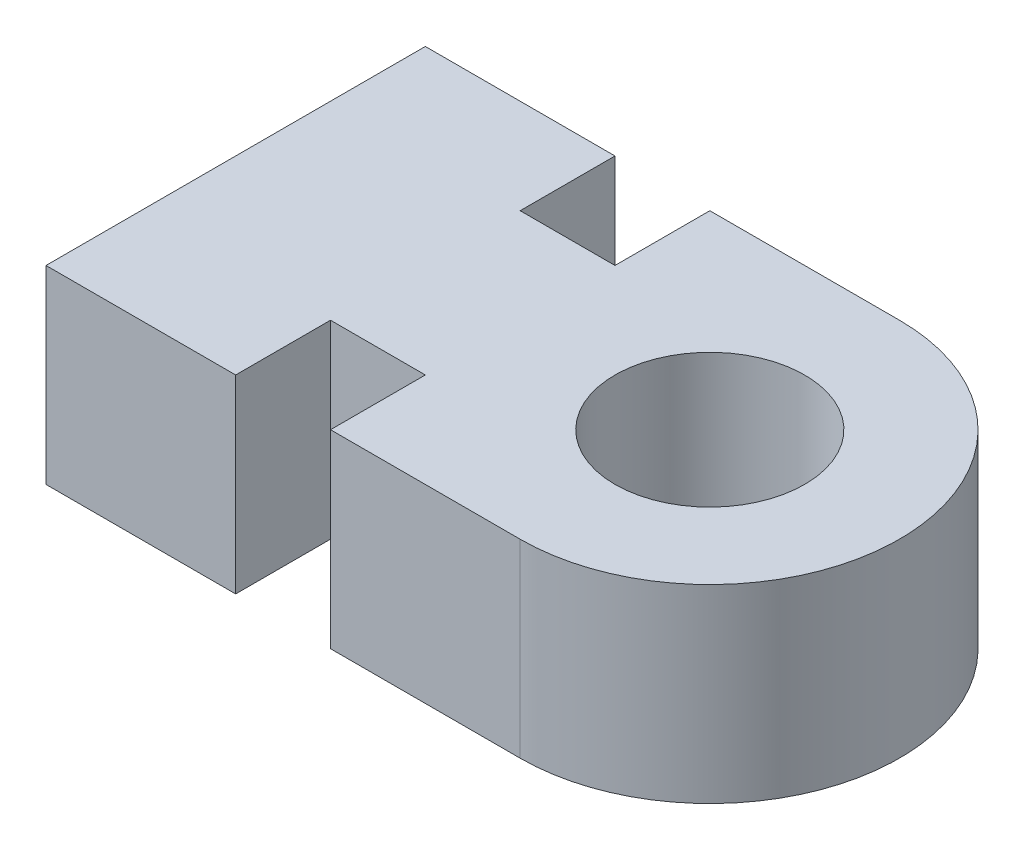
SolidWorks part; units mm, degrees
ref_plane "Front Plane" through (0, 0, 0) normal (0, 0, 1) x (1, 0, 0)
ref_plane "Top Plane" through (0, 0, 0) normal (0, 1, 0) x (1, 0, 0)
ref_plane "Right Plane" through (0, 0, 0) normal (1, 0, 0) x (0, 0, -1)
sketch "Sketch1" plane through (0, 0, 0) normal (0, 1, 0) x (1, 0, 0)
  line L0 (0, 20) -> (-20, 20)
  line L1 (-20, 20) -> (-20, 10)
  line L2 (-20, 10) -> (-30, 10)
  line L3 (-30, 10) -> (-30, 20)
  line L4 (-30, 20) -> (-50, 20)
  line L5 (-50, 20) -> (-50, -20)
  line L6 (-50, -20) -> (-30, -20)
  line L7 (-30, -20) -> (-30, -10)
  line L8 (-30, -10) -> (-20, -10)
  line L9 (-20, -10) -> (-20, -20)
  line L10 (-20, -20) -> (0, -20)
  circle A0 centre (0, 0) radius 10
  arc A1 (0, -20) -> (0, 20) centre (0, 0) ccw
  dimension "D1" = 20
  dimension "D2" = 40
  dimension "D3" = 20
  dimension "D4" = 20
  dimension "D5" = 10
  dimension "D6" = 10
  dimension "D7" = 20
  dimension "D8" = 10
extrude "Boss-Extrude1" add sketch "Sketch1" along normal blind 20
